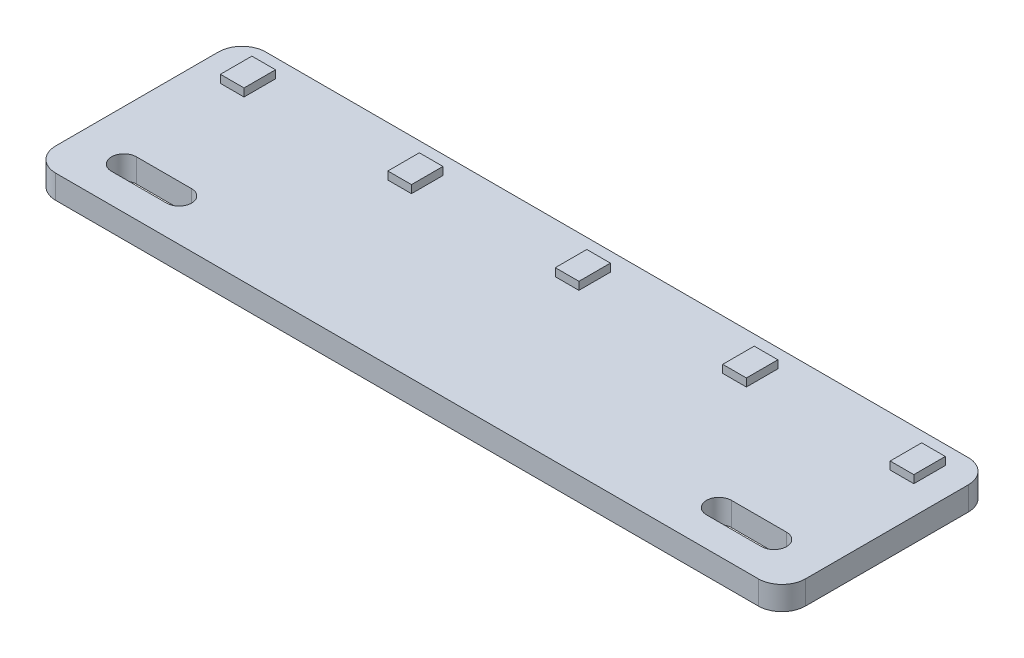
SolidWorks part; units mm, degrees
material "锰青铜"
ref_plane "前视基准面" through (0, 0, 0) normal (0, 0, 1) x (1, 0, 0)
ref_plane "上视基准面" through (0, 0, 0) normal (0, 1, 0) x (1, 0, 0)
ref_plane "右视基准面" through (0, 0, 0) normal (1, 0, 0) x (0, 0, -1)
sketch "草图1" plane through (0, 0, 0) normal (0, 1, 0) x (1, 0, 0)
  line L0 (0, 0) -> (0, -8) construction
  line L1 (-47.625, -13.335) -> (47.625, -13.335)
  line L2 (-47.625, -13.335) -> (-47.625, 13.335)
  line L3 (-47.625, 13.335) -> (47.625, 13.335)
  line L4 (47.625, -13.335) -> (47.625, 13.335)
  line L5 (-47.625, -13.335) -> (47.625, 13.335) construction
  line L6 (-47.625, 13.335) -> (47.625, -13.335) construction
  line L7 (0, -8) -> (34.29, -8) construction
  line L8 (34.29, -8) -> (41.29, -8) construction
  line L9 (34.29, -6.41) -> (41.29, -6.41)
  line L10 (34.29, -9.59) -> (41.29, -9.59)
  line L11 (-34.29, -8) -> (-41.29, -8) construction
  line L12 (-34.29, -6.41) -> (-41.29, -6.41)
  line L13 (-34.29, -9.59) -> (-41.29, -9.59)
  arc A0 (34.29, -6.41) -> (34.29, -9.59) centre (34.29, -8) ccw
  arc A1 (41.29, -9.59) -> (41.29, -6.41) centre (41.29, -8) ccw
  arc A2 (-34.29, -6.41) -> (-34.29, -9.59) centre (-34.29, -8) cw
  arc A3 (-41.29, -9.59) -> (-41.29, -6.41) centre (-41.29, -8) cw
  point P0 (0, 0)
  point P9 (37.79, -8)
  point P17 (-37.79, -8)
  dimension "D5" = 1.59
  dimension "D1" = 95.25
  dimension "D2" = 26.67
  dimension "D3" = 68.58
  dimension "D4" = 7
  dimension "D6" = 8
extrude "凸台-拉伸1" add sketch "草图1" along normal mid plane 3
fillet "圆角1" radius 3 4 edges at (-47.625, 0, 13.335) (-47.625, 0, -13.335) (47.625, 0, -13.335) (47.625, 0, 13.335)
sketch "草图2" plane through (0, 0, 0) normal (0, 1, 0) x (1, 0, 0)
  line L0 (0, 0) -> (0, 9) construction
  line L2 (-1.5, 11) -> (1.5, 11)
  line L3 (-1.5, 11) -> (-1.5, 7)
  line L4 (-1.5, 7) -> (1.5, 7)
  line L5 (1.5, 11) -> (1.5, 7)
  line L6 (-1.5, 11) -> (1.5, 7) construction
  line L7 (-1.5, 7) -> (1.5, 11) construction
  dimension "D1" = 9
  dimension "D2" = 3
  dimension "D3" = 4
extrude "凸台-拉伸2" add sketch "草图2" along normal mid plane 5
pattern_linear "阵列(线性)1" count 3 spacing 21.27 along (1, 0, 0) count 3 spacing 21.27 along (-1, 0, 0) of "凸台-拉伸2"
